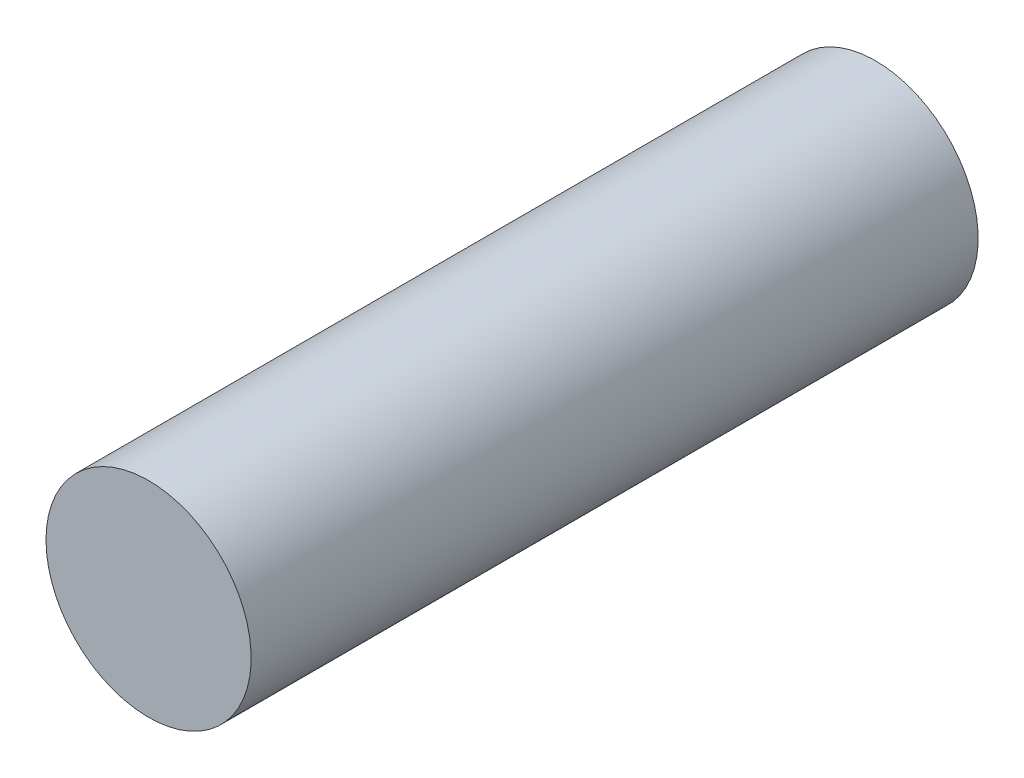
SolidWorks part; units mm, degrees
ref_plane "Front Plane" through (0, 0, 0) normal (0, 0, 1) x (1, 0, 0)
ref_plane "Top Plane" through (0, 0, 0) normal (0, 1, 0) x (1, 0, 0)
ref_plane "Right Plane" through (0, 0, 0) normal (1, 0, 0) x (0, 0, -1)
sketch "Sketch1" plane through (0, 0, 0) normal (0, 0, 1) x (1, 0, 0)
  circle A0 centre (0, 0) radius 3.2
  dimension "D1" = 6.4
extrude "Boss-Extrude1" add sketch "Sketch1" along normal blind 22.68
scale "缩放比例1" scale about centroid uniform scaling yes scale factor 2
